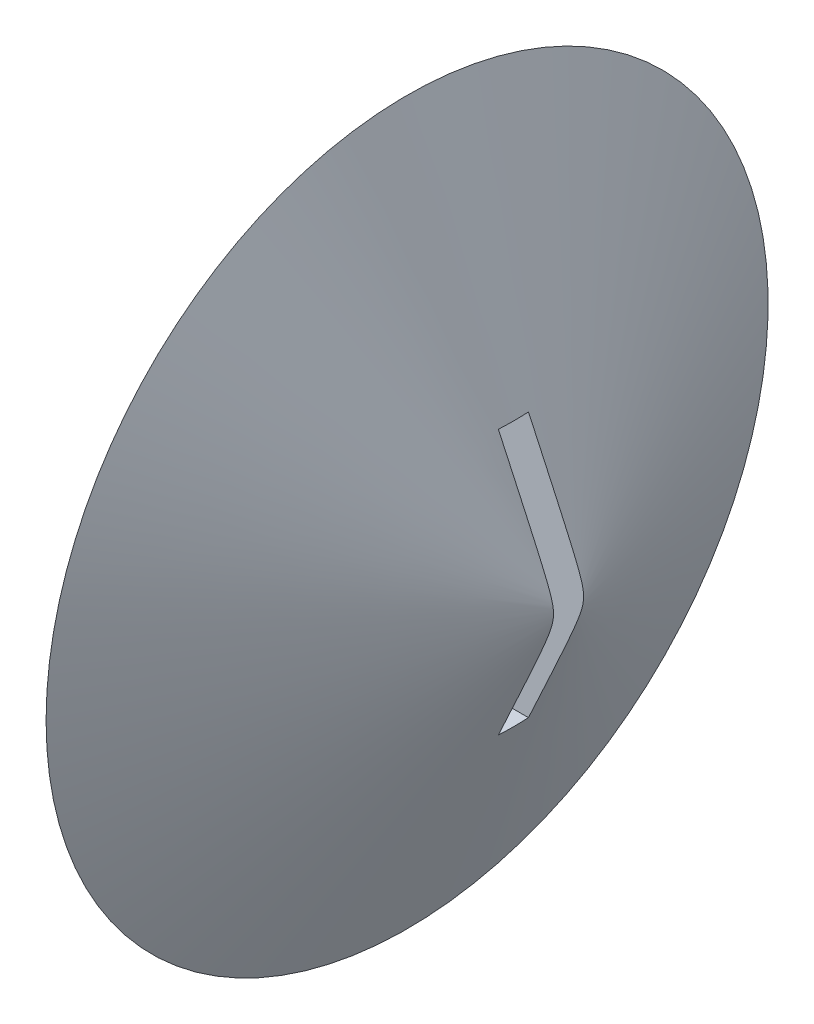
SolidWorks part; units mm, degrees
ref_plane "前视基准面" through (0, 0, 0) normal (0, 0, 1) x (1, 0, 0)
ref_plane "上视基准面" through (0, 0, 0) normal (0, 1, 0) x (1, 0, 0)
ref_plane "右视基准面" through (0, 0, 0) normal (1, 0, 0) x (0, 0, -1)
sketch "草图1" plane through (0, 0, 0) normal (0, 0, 1) x (1, 0, 0)
  line L0 (-948.0871, 0) -> (46456.2673, 0) construction
  line L1 (0, -948.0871) -> (0, 46456.2673) construction
  line L2 (0, 0) -> (-14, 0)
  line L3 (-14, 0) -> (-14, 30)
  line L4 (-14, 30) -> (0, 0)
  dimension "D1" = 14
  dimension "D2" = 30
revolve "旋转1" add sketch "草图1" angle 360 mid plane about L0
sketch "草图2" plane through (-14, 0, 0) normal (-1, 0, 0) x (0, 0, 1)
  line L0 (-1000, 0) -> (49000, 0) construction
  line L1 (0, -1000) -> (0, 49000) construction
  line L2 (1.25, 11) -> (-1.25, 11)
  line L3 (-1.25, 11) -> (-1.25, 0)
  line L5 (1.25, 11) -> (1.25, -11)
  line L6 (1.25, -11) -> (-1.25, -11)
  line L7 (-1.25, 0) -> (-1.25, -11)
  dimension "D1" = 1.25
  dimension "D2" = 2.5
  dimension "D3" = 11
  dimension "D4" = 22
extrude "切除-拉伸1" cut sketch "草图2" against normal through all
